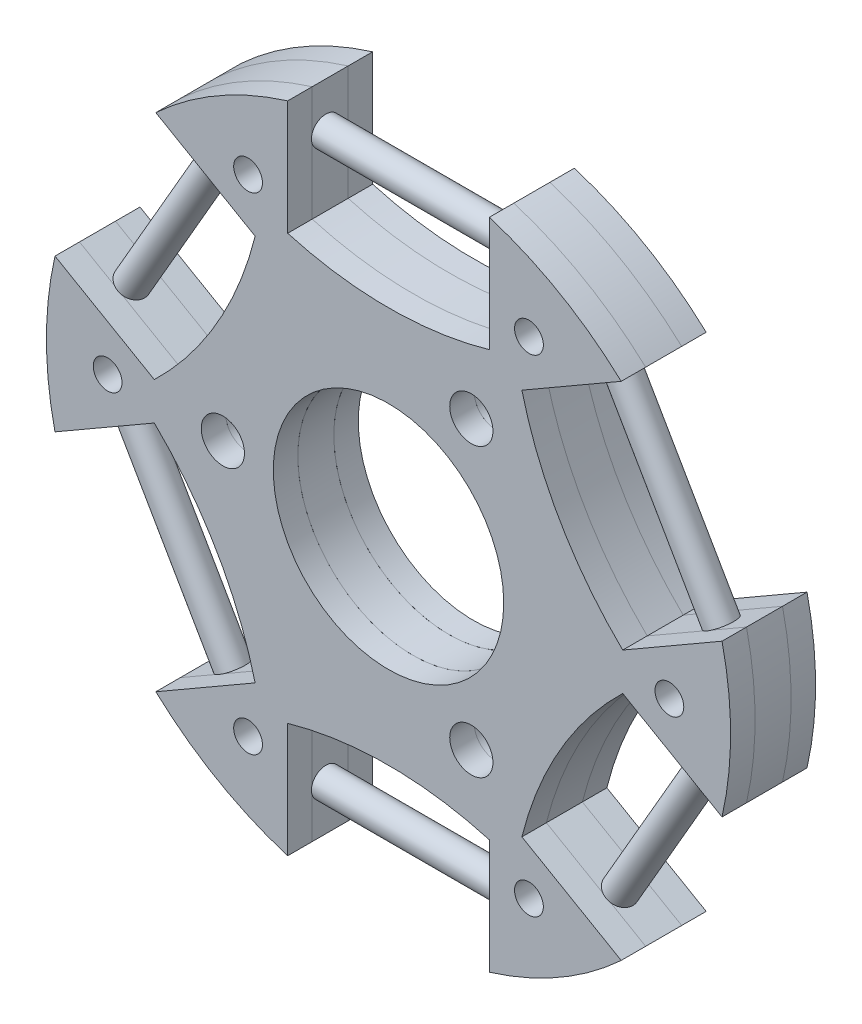
SolidWorks part; units mm, degrees
material "AISI 304"
ref_plane "前视基准面" through (0, 0, 0) normal (0, 0, 1) x (1, 0, 0)
ref_plane "上视基准面" through (0, 0, 0) normal (0, 1, 0) x (1, 0, 0)
ref_plane "右视基准面" through (0, 0, 0) normal (1, 0, 0) x (0, 0, -1)
sketch "草图1" plane through (0, 0, 0) normal (0, 0, 1) x (1, 0, 0)
  circle A0 centre (0, 0) radius 25.4
  circle A1 centre (0, 0) radius 8
  dimension "D1" = 50.8
  dimension "D2" = 16
extrude "凸台-拉伸1" add sketch "草图1" along normal blind 1.7
sketch "草图2" plane through (0, 0, 1.7) normal (0, 0, 1) x (1, 0, 0)
  circle A0 centre (0, 0) radius 25.4
  circle A1 centre (0, 0) radius 3.5
  dimension "D1" = 7
extrude "凸台-拉伸2" add sketch "草图2" along normal blind 2.5 separate body
sketch "草图3" plane through (0, 0, 4.2) normal (0, 0, 1) x (1, 0, 0)
  circle A0 centre (0, 0) radius 25.4
  circle A1 centre (0, 0) radius 8
  dimension "D1" = 16
extrude "凸台-拉伸3" add sketch "草图3" along normal blind 1.7 separate body
sketch "草图4" plane through (0, 0, 5.9) normal (0, 0, 1) x (1, 0, 0)
  line L0 (9.2597, 13.429) -> (17.6452, 18.2704)
  line L1 (7, 14.7336) -> (7, 24.4164)
  line L2 (-7, 14.7336) -> (-7, 24.4164)
  line L3 (16.2597, 1.3046) -> (24.6452, 6.146)
  line L4 (16.2597, -1.3046) -> (24.6452, -6.146)
  line L5 (9.2597, -13.429) -> (17.6452, -18.2704)
  line L6 (7, -14.7336) -> (7, -24.4164)
  line L7 (-7, -14.7336) -> (-7, -24.4164)
  line L8 (-9.2597, -13.429) -> (-17.6452, -18.2704)
  line L9 (-16.2597, -1.3046) -> (-24.6452, -6.146)
  line L10 (-16.2597, 1.3046) -> (-24.6452, 6.146)
  line L11 (-9.2597, 13.429) -> (-17.6452, 18.2704)
  arc A0 (7, 24.4164) -> (-7, 24.4164) centre (0, 0) ccw
  arc A1 (9.2597, 13.429) -> (16.2597, 1.3046) centre (33.9049, 19.575) ccw
  arc A2 (-7, 14.7336) -> (7, 14.7336) centre (0, 39.15) ccw
  arc A3 (24.6452, 6.146) -> (17.6452, 18.2704) centre (0, 0) ccw
  arc A4 (16.2597, -1.3046) -> (9.2597, -13.429) centre (33.9049, -19.575) ccw
  arc A5 (17.6452, -18.2704) -> (24.6452, -6.146) centre (0, 0) ccw
  arc A6 (7, -14.7336) -> (-7, -14.7336) centre (0, -39.15) ccw
  arc A7 (-7, -24.4164) -> (7, -24.4164) centre (0, 0) ccw
  arc A8 (-9.2597, -13.429) -> (-16.2597, -1.3046) centre (-33.9049, -19.575) ccw
  arc A9 (-24.6452, -6.146) -> (-17.6452, -18.2704) centre (0, 0) ccw
  arc A10 (-16.2597, 1.3046) -> (-9.2597, 13.429) centre (-33.9049, 19.575) ccw
  arc A11 (-17.6452, 18.2704) -> (-24.6452, 6.146) centre (0, 0) ccw
  point P34 (0, 0)
  dimension "D1" = 50.8
  dimension "D2" = 6
  dimension "D3" = 50.8
extrude "切除-拉伸1" cut sketch "草图4" against normal blind 20.5
sketch "草图5" plane through (0, 0, 5.9) normal (0, 0, 1) x (1, 0, 0)
  circle A2 centre (9.75, 16.8875) radius 1
  circle A3 centre (19.5, 0) radius 1
  circle A4 centre (9.75, -16.8875) radius 1
  circle A5 centre (-9.75, -16.8875) radius 1
  circle A6 centre (-19.5, 0) radius 1
  circle A7 centre (-9.75, 16.8875) radius 1
  point P21 (0, 0)
  dimension "D2" = 2
  dimension "D3" = 6
extrude "切除-拉伸2" cut sketch "草图5" against normal blind 20.5
sketch "草图6" plane through (-7, 0, 0) normal (1, 0, 0) x (0, 0, -1)
  circle A0 centre (-3.25, 19.575) radius 1
  dimension "D1" = 2
extrude "凸台-拉伸4" add sketch "草图6" along normal blind 14
pattern_circular "阵列(圆周)1" count 6 over 360 about axis through (0, 0, 0) along (0, 0, 1) of "凸台-拉伸4"
sketch "草图7" plane through (0, 0, 4.2) normal (0, 0, 1) x (1, 0, 0)
  circle A1 centre (0, 7) radius 1
  circle A2 centre (7, 0) radius 1
  circle A3 centre (0, -7) radius 1
  circle A4 centre (-7, 0) radius 1
  point P14 (0, 0)
  dimension "D2" = 2
  dimension "D3" = 4
extrude "切除-拉伸3" cut sketch "草图7" against normal blind 14
sketch "草图8" plane through (0, 0, 5.9) normal (0, 0, 1) x (1, 0, 0)
  circle A0 centre (0, 0) radius 23.75
  circle A1 centre (0, 0) radius 25.4
  dimension "D1" = 47.5
extrude "切除-拉伸4" cut sketch "草图8" against normal blind 10
sketch "草图9" plane through (0, 0, 1.7) normal (0, 0, -1) x (-1, 0, 0)
  circle A0 centre (0, 0) radius 8
  dimension "D1" = 16
extrude "切除-拉伸5" cut sketch "草图9" against normal through all
sketch "草图10" plane through (0, 0, 0) normal (0, 0, -1) x (-1, 0, 0)
  line L0 (-5.75, 9.9593) -> (0, 0) construction
  line L1 (0, 11.5) -> (0, -0.3066) construction
  circle A0 centre (0, 0) radius 11.5 construction
  circle A1 centre (-5.75, 9.9593) radius 1.5
  circle A2 centre (11.5, 0) radius 1.5
  circle A3 centre (-5.75, -9.9593) radius 1.5
  point P5 (-5.75, 9.9593)
  point P6 (0, -10.6196)
  point P13 (0, 0)
  point P14 (0, 0)
  dimension "D1" = 23
  dimension "D2" = 3
  dimension "D3" = 30
  dimension "D4" = 3
extrude "切除-拉伸6" cut sketch "草图10" against normal through all
